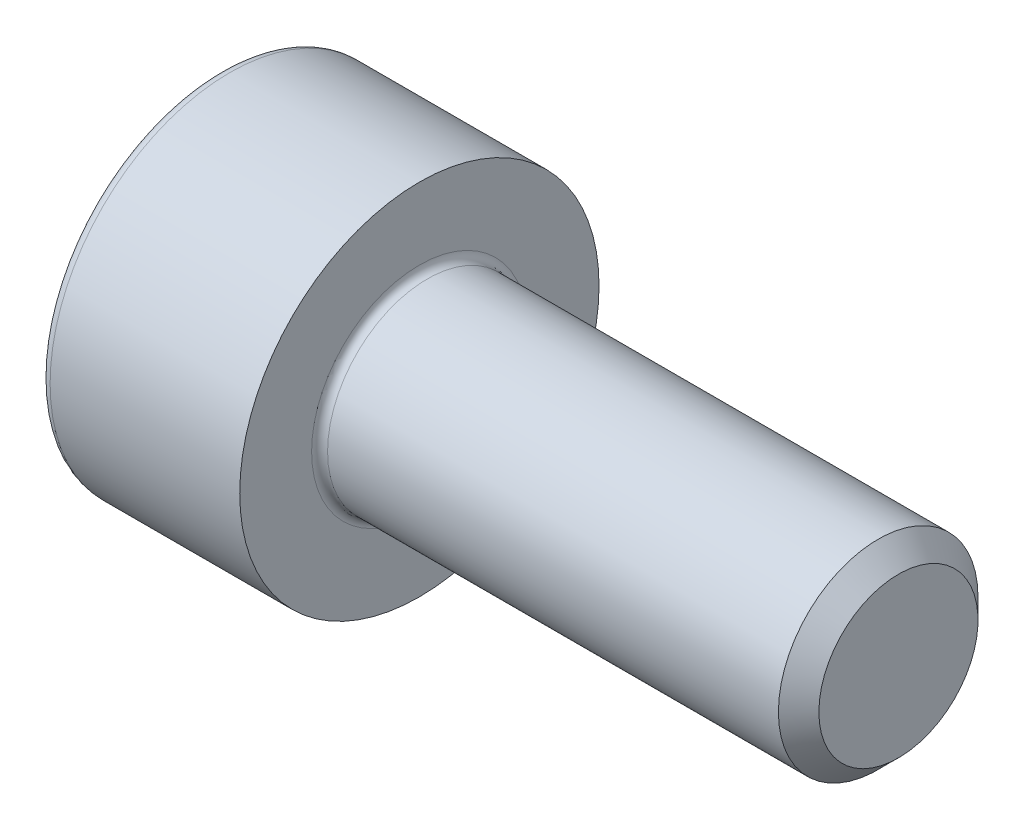
SolidWorks part; units mm, degrees
revolve "Base-Revolve" add sketch "BodySke"
sketch "BodySke" plane through (0, 0, 0) normal (0, 0, 1) x (1, 0, 0)
  line L0 (0, 0) -> (0, 2.25)
  line L1 (0, 2.25) -> (2.5, 2.25)
  line L2 (2.5, 2.25) -> (2.5, 1.25)
  line L3 (2.5, 1.25) -> (8.2465, 1.25)
  line L4 (8.5, 0.9965) -> (8.5, 0)
  line L5 (8.5, 0) -> (0, 0)
  line L6 (-31.75, 0) -> (127, 0) construction
  line L8 (8.5, 0.9965) -> (8.2465, 1.25)
  line L10 (8.5, -0.9965) -> (8.2465, -1.25) construction
  line L11 (2.95, 9.525) -> (2.95, 3.175) construction
  line L12 (2.5, 9.525) -> (2.5, 3.175) construction
  line L13 (-51.5, 9.525) -> (-51.5, 3.175) construction
  dimension "Head_ht" = 2.5
  dimension "Length" = 6
  dimension "Body_ch_ang" = 45
  dimension "Diameter" = 2.5
  dimension "Minor_dia" = 1.993
  dimension "Advance" = 0.45
  dimension "Thread_nom" = 6
  dimension "Thread_length" = 60
  dimension "Head_dia" = 4.5
cosmetic thread "ThreadCosmetic" [suppressed]
fillet "Fillet1" radius 0.1 1 edges at (2.5, 0, 1.25)
fillet "Fillet2" radius 0.125 1 edges at (0, 0, 2.25)
ref_plane "Plane1" through (0, 0, 0) normal (0, 0, 1) x (1, 0, 0)
ref_plane "Plane2" through (0, 0, 0) normal (0, 1, 0) x (1, 0, 0)
ref_plane "Plane3" through (0, 0, 0) normal (1, 0, 0) x (0, 0, -1)
sketch "Sketch2" plane through (0, 0, 0) normal (0, 0, 1) x (1, 0, 0)
  line L0 (0, 1.0225) -> (1.1, 1.0225)
  line L1 (1.1, 1.0225) -> (1.6903, 0)
  line L2 (-31.75, 0) -> (127, 0) construction
  line L3 (1.6903, 0) -> (0, 0)
  line L4 (0, 0) -> (0, 1.0225)
  line L6 (0, 0) -> (47.625, 0) construction
  dimension "D1" = 1.0225
  dimension "D2" = 60
  dimension "Depth" = 1.1
revolve "Hex-PreBroach" cut sketch "Sketch2" angle 360 about L6
sketch "Sketch3" plane through (0, 0, 0) normal (-1, 0, 0) x (0, 0.5, 0.866)
  line L0 (0.5903, 1.0225) -> (-0.5903, 1.0225)
  line L1 (-0.5903, 1.0225) -> (-1.1807, 0)
  line L2 (0.5903, 1.0225) -> (1.1807, 0)
  line L3 (0.5903, -1.0225) -> (1.1807, 0)
  line L4 (0.5903, -1.0225) -> (-0.5903, -1.0225)
  line L5 (-0.5903, -1.0225) -> (-1.1807, 0)
  dimension "D1" = 1.0225
  dimension "D2" = 1.0225
  dimension "Hex_size" = 2.045
extrude "Hex" cut sketch "Sketch3" against normal blind 1.1
sketch "ThdSchSke" plane through (0, 0, 0) normal (0, 0, 1) x (1, 0, 0)
  line L0 (3.85, -0.9965) -> (3.6725, -1.25)
  line L1 (3.85, -0.9965) -> (4.0275, -1.25)
  line L2 (4.0275, -1.25) -> (4.0275, -1.5625)
  line L3 (-3.175, 0) -> (5.1513, 0) construction
  line L4 (0, 2.125) -> (0, -2.125) construction
  line L5 (4.0275, -1.5625) -> (3.6725, -1.5625)
  line L6 (3.6725, -1.5625) -> (3.6725, -1.25)
  dimension "Thread_minor" = 1.993
  dimension "Diameter" = 2.5
  dimension "Start" = 3.85
revolve "ThreadSchematic" [suppressed] cut sketch "ThdSchSke" angle 360 about L3
pattern_linear "ThdSchPat" [suppressed]
equation "\"D2@Sketch3\" = \"Hex_size@Sketch3\" / 2"
equation "\"D1@Sketch3\" = \"Hex_size@Sketch3\" / 2"
equation "\"D1@Sketch2\" = \"Hex_size@Sketch3\" / 2"
equation "\"Thread_minor@ThreadCosmetic\"  =  \"Minor_dia@BodySke\""
equation "\"Depth@Sketch2\" =  \"Key_eng@Hex\""
equation "\"Thread_length@ThreadCosmetic\" = ((sgn( (\"Length@BodySke\" - \"Advance@BodySke\" * 3.0) - \"Thread_nom@BodySke\" )-1)*( (\"Length@BodySke\" - \"Advance@BodySke\" * 3.0) - \"Thread_nom@BodySke\" ))/-2+ \"Thread_nom@BodySke\""
equation "\"Thread_minor@ThdSchSke\" = \"Minor_dia@BodySke\""
equation "\"Diameter@ThdSchSke\" = \"Diameter@BodySke\""
equation "\"Overcut@ThdSchSke\" = \"Diameter@BodySke\" * 1.25"
equation "\"Start@ThdSchSke\" = \"Head_ht@BodySke\" + \"Length@BodySke\" - \"Thread_length@ThreadCosmetic\"  '---Non-countersunk---"
equation "\"Num_threads@ThdSchPat\" = int( \"Thread_length@ThreadCosmetic\" / \"Advance@BodySke\" + 0.999 )  + 1"
equation "\"Advance@ThdSchPat\" = \"Thread_length@ThreadCosmetic\" /  (\"Num_threads@ThdSchPat\" - 1) 'relax it"
equation "\"Num_threads@ThdSchPat\" = \"Num_threads@ThdSchPat\" - sgn( \"Num_threads@ThdSchPat\" - 1) '---chamfered tips only---"
